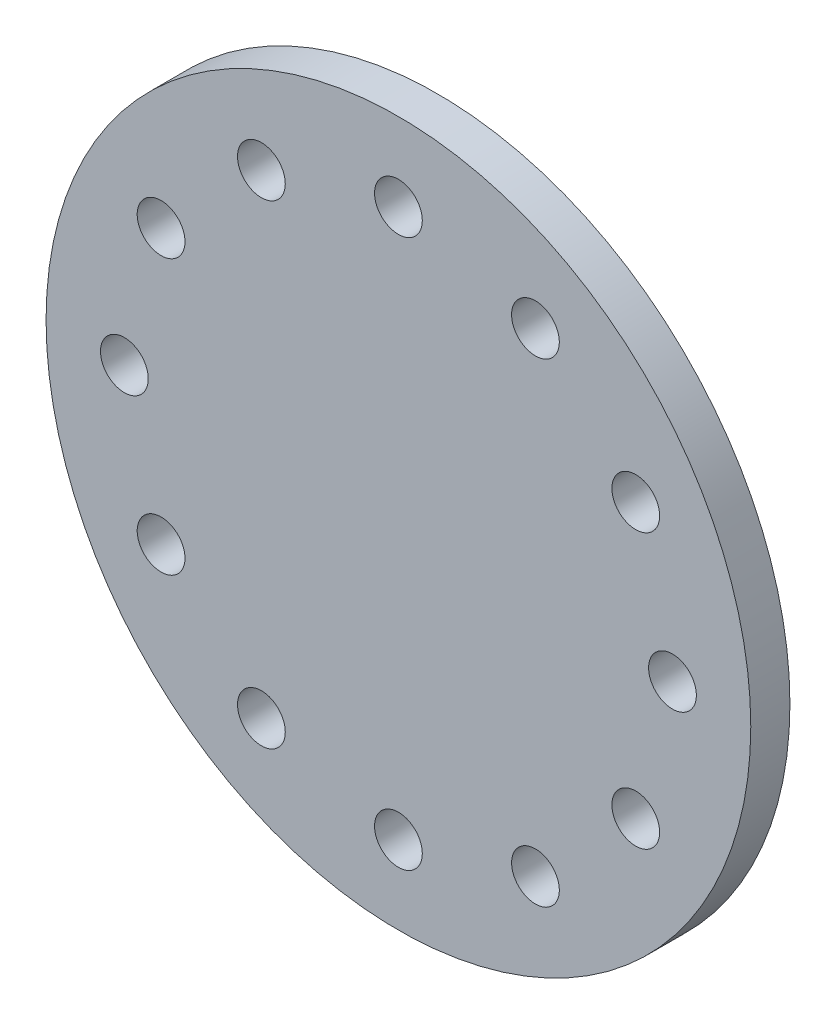
SolidWorks part; units mm, degrees
ref_plane "Front Plane" through (0, 0, 0) normal (0, 0, 1) x (1, 0, 0)
ref_plane "Top Plane" through (0, 0, 0) normal (0, 1, 0) x (1, 0, 0)
ref_plane "Right Plane" through (0, 0, 0) normal (1, 0, 0) x (0, 0, -1)
sketch "Sketch1" plane through (0, 0, 0) normal (0, 0, 1) x (1, 0, 0)
  line L1 (-45, -45) -> (45, -45) construction
  line L2 (-45, -45) -> (-45, 45) construction
  line L3 (-45, 45) -> (45, 45) construction
  line L4 (45, -45) -> (45, 45) construction
  line L5 (-45, -45) -> (45, 45) construction
  line L6 (-45, 45) -> (45, -45) construction
  circle A0 centre (0, 0) radius 45
  point P0 (0, 0)
  dimension "D1" = 90
extrude "Boss-Extrude1" add sketch "Sketch1" along normal blind 5
hole_wizard "Ø6.1 (6.1) Diameter Hole1" positions "Sketch3" profile "Sketch2" hole size "Ø6.1" standard "DIN"
sketch "Sketch3" plane through (0, 0, 5) normal (0, 0, 1) x (1, 0, 0)
  line L0 (-45, 0) -> (45, 0) construction
  circle A0 centre (0, 0) radius 45 construction
  point P0 (-35, 0)
  point P51 (-30.3109, 17.5)
  point P52 (-17.5, 30.3109)
  point P53 (0, 35)
  point P54 (17.5, 30.3109)
  point P55 (30.3109, 17.5)
  point P56 (35, 0)
  point P57 (30.3109, -17.5)
  point P58 (17.5, -30.3109)
  point P59 (0, -35)
  point P60 (-17.5, -30.3109)
  point P61 (-30.3109, -17.5)
  dimension "D1" = 10
  dimension "D2" = 12
sketch "Sketch2" plane through (-35, 0, 5) normal (1, 0, 0) x (0, -1, 0)
  line L0 (0, 0) -> (0, 11.8326)
  line L1 (0, 11.8326) -> (3.05, 10)
  line L2 (3.05, 10) -> (3.05, 0)
  line L5 (3.05, 0) -> (0, 0)
  line L10 (0, 11.8326) -> (-3.05, 10) construction
  line L11 (0, -6.35) -> (0, 107.95) construction
  dimension "Hole Dia." = 6.1
  dimension "Hole Depth" = 10
  dimension "Drill Angle" = 118
